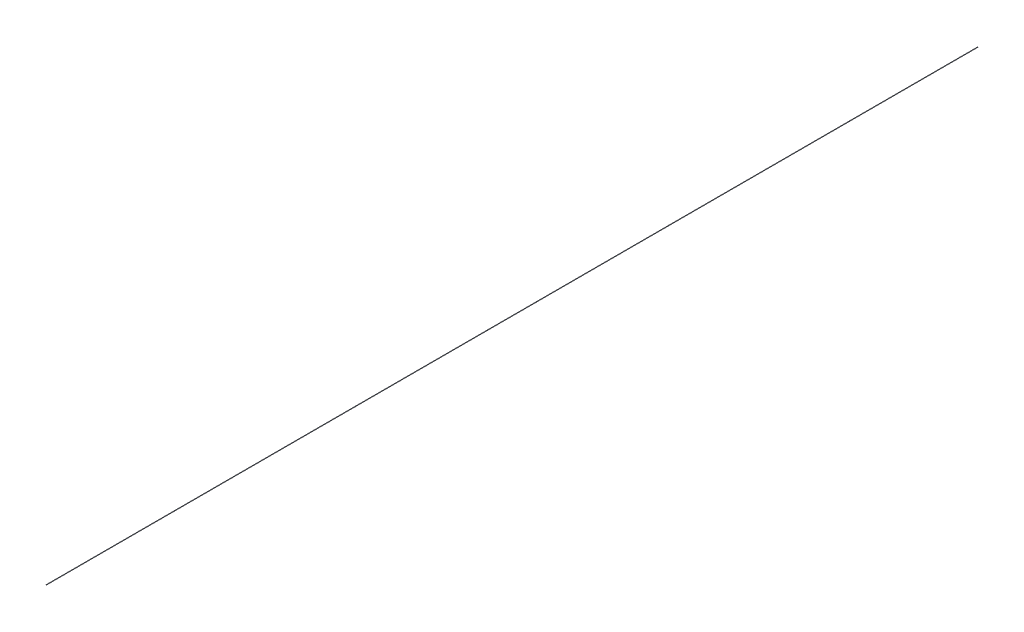
SolidWorks part; units mm, degrees
ref_plane "Front Plane" through (0, 0, 0) normal (0, 0, 1) x (1, 0, 0)
ref_plane "Top Plane" through (0, 0, 0) normal (0, 1, 0) x (1, 0, 0)
ref_plane "Right Plane" through (0, 0, 0) normal (1, 0, 0) x (0, 0, -1)
sketch "Sketch3" plane through (0, 0, 0) normal (0, 0, 1) x (1, 0, 0)
  circle A0 centre (0, 0) radius 0.5
  dimension "D1" = 1
extrude "Boss-Extrude1" add sketch "Sketch3" along normal mid plane 3025
fillet "Fillet1" radius 0.4 2 edges at (0.5, 0, 1512.5) (0.5, 0, -1512.5)
